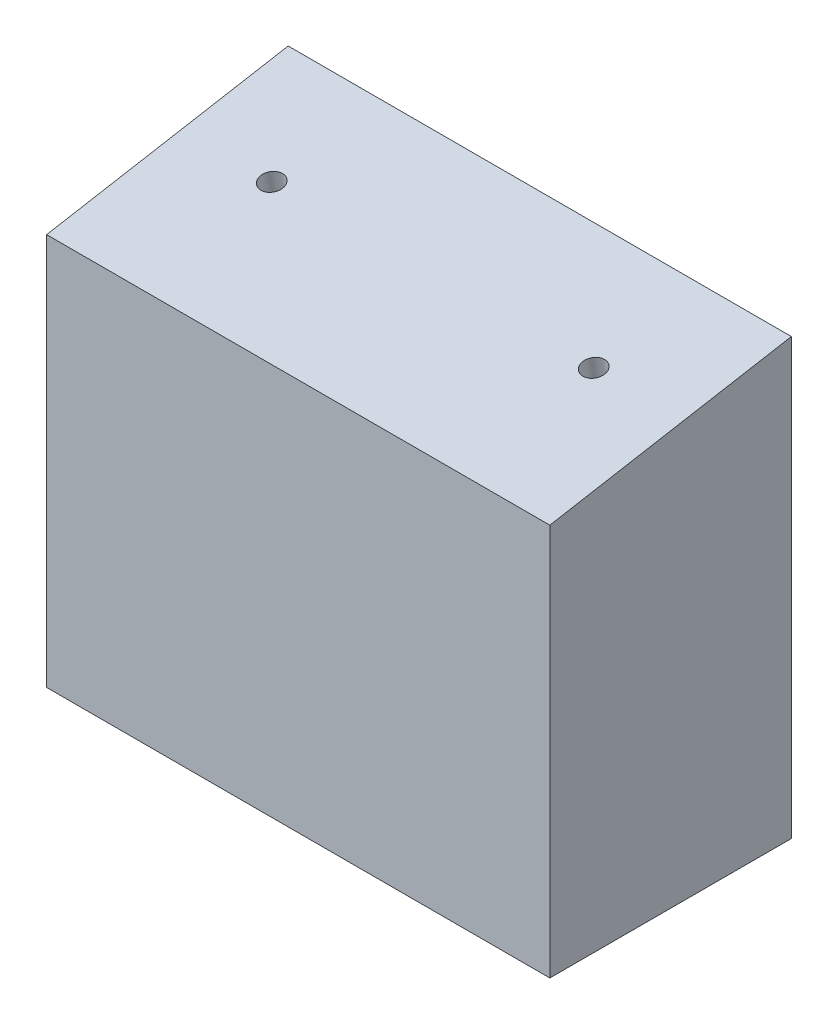
SolidWorks part; units mm, degrees
material "ABS"
ref_plane "Front Plane" through (0, 0, 0) normal (0, 0, 1) x (1, 0, 0)
ref_plane "Top Plane" through (0, 0, 0) normal (0, 1, 0) x (1, 0, 0)
ref_plane "Right Plane" through (0, 0, 0) normal (1, 0, 0) x (0, 0, -1)
sketch "Sketch3" plane through (0, 0, 0) normal (1, 0, 0) x (0, 0, -1)
  line L0 (0, 0) -> (38.1, 0)
  line L1 (38.1, 0) -> (38.1, 68.58)
  line L2 (38.1, 68.58) -> (0, 61.8619)
  line L3 (0, 61.8619) -> (0, 0)
  dimension "D1" = 10
  dimension "D2" = 68.58
  dimension "D3" = 38.1
extrude "Boss-Extrude2" add sketch "Sketch3" along normal mid plane 79.375
sketch "Sketch4" plane through (0, 0, 0) normal (0, -1, 0) x (1, 0, 0)
  line L0 (-39.6875, -19.05) -> (39.6875, -19.05) construction
  line L1 (-39.6875, 0) -> (-39.6875, -38.1) construction
  line L2 (39.6875, 0) -> (39.6875, -38.1) construction
  line L3 (0, 0) -> (0, -38.1) construction
  line L4 (39.6875, -38.1) -> (-39.6875, -38.1) construction
  point P6 (-25.4, -19.05)
  point P12 (25.4, -19.05)
  dimension "D1" = 25.4
hole_wizard "1/4-20 Tapped Hole1" positions "Sketch5" profile "Sketch6" tap size "1/4-20" standard "ANSI Inch"
sketch "Sketch5" plane through (0, 0, 0) normal (0, -1, 0) x (-1, 0, 0)
  point P0 (25.4, 19.05)
  point P3 (-25.4, 19.05)
sketch "Sketch6" plane through (-25.4, 0, -19.05) normal (1, 0, 0) x (0, 0, -1)
  line L0 (0, 0) -> (0, 24.3938)
  line L1 (0, 24.3938) -> (2.5527, 22.86)
  line L2 (2.5527, 22.86) -> (2.5527, 0)
  line L5 (2.5527, 0) -> (0, 0)
  line L10 (0, 24.3938) -> (-2.5527, 22.86) construction
  line L11 (0, -6.35) -> (0, 107.95) construction
  dimension "Tap Drill Dia." = 5.1054
  dimension "Tap Drill Depth" = 22.86
  dimension "Drill Angle" = 118
cosmetic thread "Hole Thread1" parameters "D1"=19.05, "D2"=6.35
cosmetic thread "Hole Thread2" parameters "D1"=19.05, "D2"=6.35
sketch "Sketch7" plane through (0, 59.9966, 10.579) normal (0, 0.9848, 0.1736) x (1, 0, 0)
  line L0 (-39.6875, 32.285) -> (39.6875, 32.285) construction
  line L1 (-39.6875, 49.43) -> (-39.6875, 10.7422) construction
  line L2 (39.6875, 49.43) -> (39.6875, 10.7422) construction
  line L3 (0, 10.7422) -> (0, 49.43) construction
  line L4 (39.6875, 10.7422) -> (-39.6875, 10.7422) construction
  line L5 (39.6875, 49.43) -> (-39.6875, 49.43) construction
  point P6 (-25.4, 32.285)
  point P7 (25.4, 32.285)
  dimension "D1" = 50.8
  dimension "D2" = 17.145
hole_wizard "#8-32 Tapped Hole1" positions "Sketch8" profile "Sketch9" tap size "#8-32" standard "ANSI Inch"
sketch "Sketch8" plane through (0, 59.9966, 10.579) normal (0, 0.9848, 0.1736) x (1, 0, 0)
  point P0 (-25.4, 32.285)
  point P3 (25.4, 32.285)
sketch "Sketch9" plane through (-25.4, 65.6028, -21.2155) normal (1, 0, 0) x (0, -0.1736, 0.9848)
  line L0 (0, 0) -> (0, 16.0238)
  line L1 (0, 16.0238) -> (1.7272, 14.986)
  line L2 (1.7272, 14.986) -> (1.7272, 0)
  line L5 (1.7272, 0) -> (0, 0)
  line L10 (0, 16.0238) -> (-1.7272, 14.986) construction
  line L11 (0, -6.35) -> (0, 107.95) construction
  dimension "Tap Drill Dia." = 3.4544
  dimension "Tap Drill Depth" = 14.986
  dimension "Drill Angle" = 118
cosmetic thread "Hole Thread3" parameters "D1"=12.7, "D2"=4.1656
cosmetic thread "Hole Thread4" parameters "D1"=12.7, "D2"=4.1656
